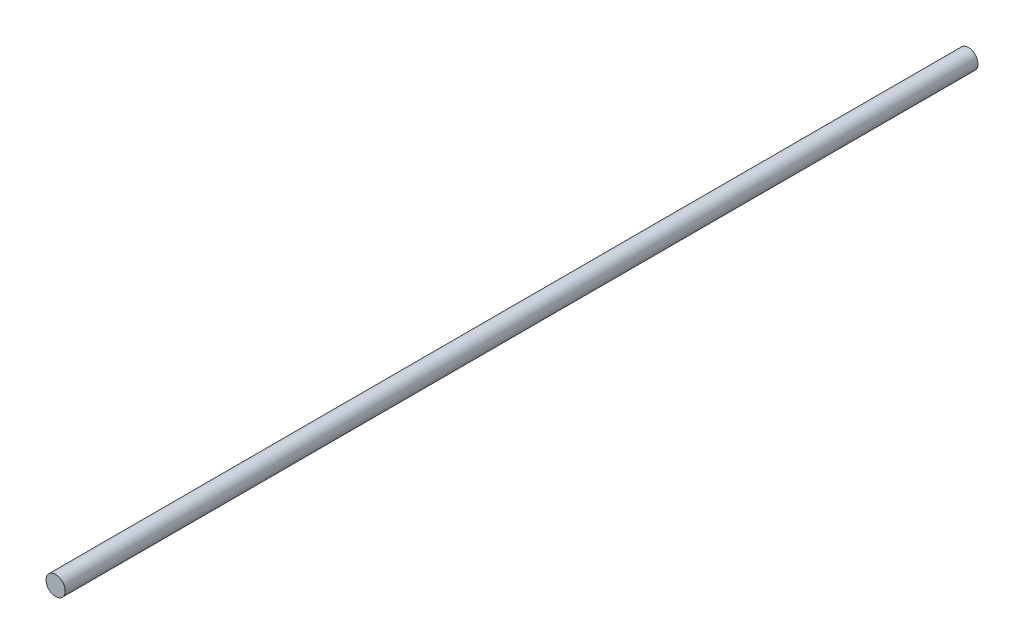
SolidWorks part; units mm, degrees
ref_plane "Front Plane" through (0, 0, 0) normal (0, 0, 1) x (1, 0, 0)
ref_plane "Top Plane" through (0, 0, 0) normal (0, 1, 0) x (1, 0, 0)
ref_plane "Right Plane" through (0, 0, 0) normal (1, 0, 0) x (0, 0, -1)
sketch "Sketch1" plane through (0, 0, 0) normal (0, 0, 1) x (1, 0, 0)
  circle A1 centre (20, 0) radius 1
extrude "Boss-Extrude1" add sketch "Sketch1" against normal blind 95
